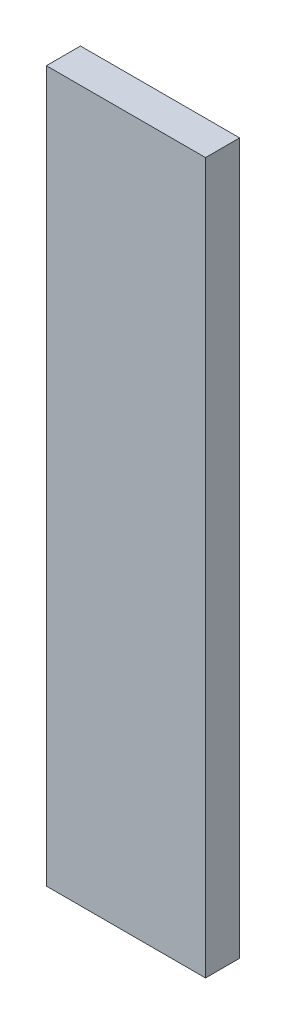
SolidWorks part; units mm, degrees
ref_plane "Alzado" through (0, 0, 0) normal (0, 0, 1) x (1, 0, 0)
ref_plane "Planta" through (0, 0, 0) normal (0, 1, 0) x (1, 0, 0)
ref_plane "Vista lateral" through (0, 0, 0) normal (1, 0, 0) x (0, 0, -1)
sketch "Croquis1" plane through (0, 0, 0) normal (0, 0, 1) x (1, 0, 0)
  line L1 (0, 0) -> (28, 0)
  line L2 (0, 0) -> (0, 125)
  line L3 (0, 125) -> (28, 125)
  line L4 (28, 0) -> (28, 125)
  dimension "D1" = 125
  dimension "D2" = 28
extrude "Saliente-Extruir1" add sketch "Croquis1" along normal blind 6
